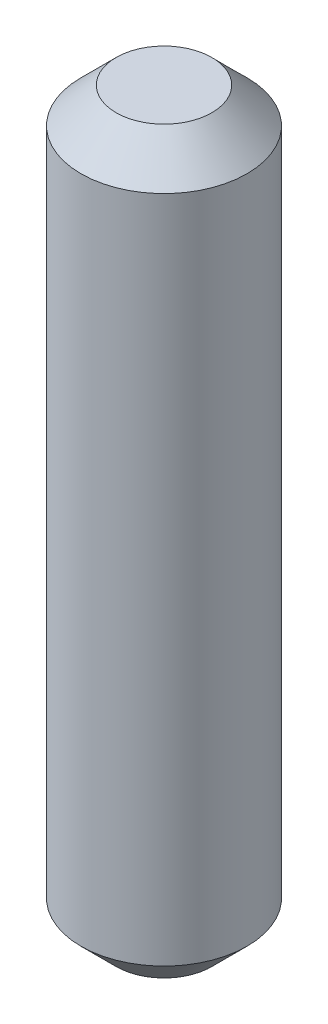
SolidWorks part; units mm, degrees
ref_plane "Front Plane" through (0, 0, 0) normal (0, 0, 1) x (1, 0, 0)
ref_plane "Top Plane" through (0, 0, 0) normal (0, 1, 0) x (1, 0, 0)
ref_plane "Right Plane" through (0, 0, 0) normal (1, 0, 0) x (0, 0, -1)
sketch "Sketch2" plane through (0, 0, 0) normal (0, 1, 0) x (1, 0, 0)
  circle A0 centre (0, 0) radius 2.9972
  dimension "D1" = 5.9944
extrude "Boss-Extrude1" add sketch "Sketch2" along normal blind 26.67
chamfer "Chamfer1" distance 1.27 angle 45 2 edges at (0, 26.67, 2.9972) (0, 0, 2.9972)
